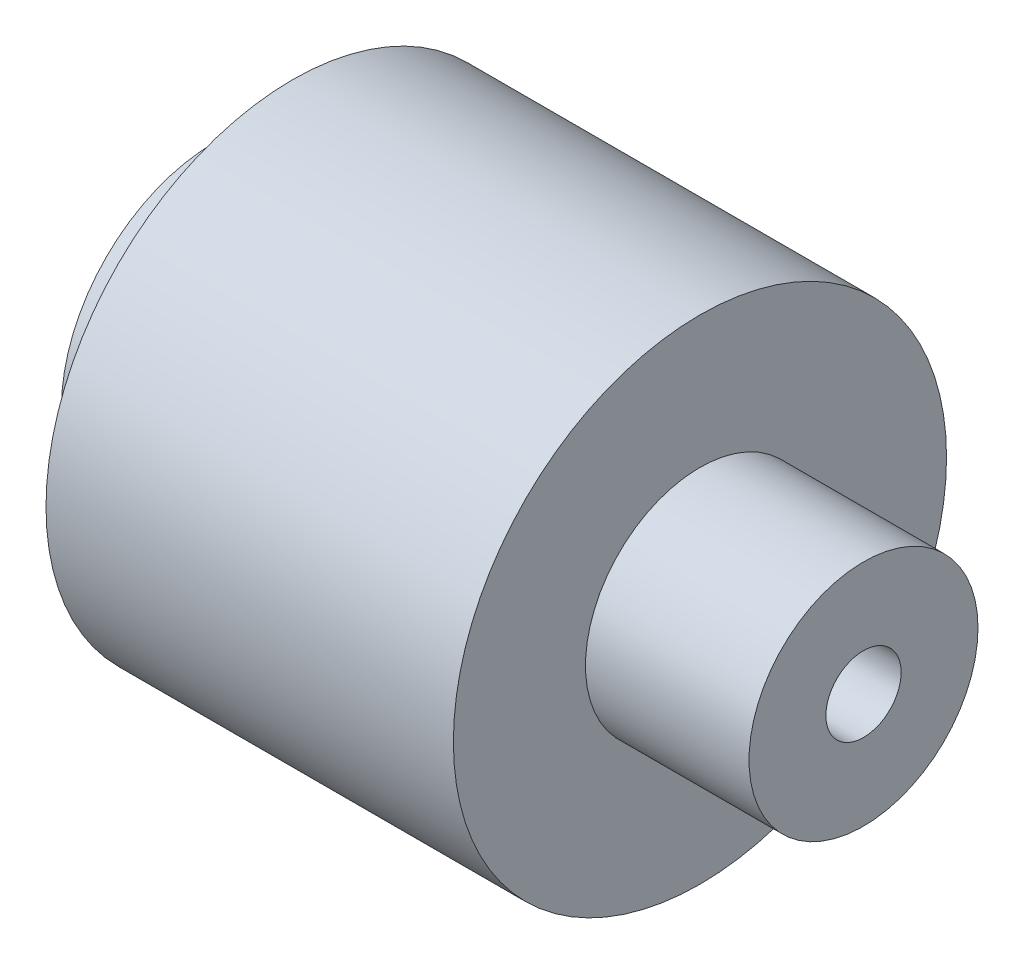
SolidWorks part; units mm, degrees
ref_plane "Front Plane" through (0, 0, 0) normal (0, 0, 1) x (1, 0, 0)
ref_plane "Top Plane" through (0, 0, 0) normal (0, 1, 0) x (1, 0, 0)
ref_plane "Right Plane" through (0, 0, 0) normal (1, 0, 0) x (0, 0, -1)
sketch "Sketch1" plane through (0, 0, 0) normal (1, 0, 0) x (0, 0, -1)
  circle A0 centre (0, 0) radius 15.0762
  dimension "D1" = 30.1523
extrude "Boss-Extrude1" add sketch "Sketch1" along normal blind 34.9072
sketch "Sketch2" plane through (0, 0, 0) normal (-1, 0, 0) x (0, 0, 1)
  circle A0 centre (0, 0) radius 4.5847
  circle A1 centre (0, 0) radius 9.3853
  dimension "D1" = 18.7706
  dimension "D2" = 9.1694
extrude "Boss-Extrude2" add sketch "Sketch2" along normal blind 4.7498
sketch "Sketch3" plane through (34.9072, 0, 0) normal (1, 0, 0) x (0, 0, -1)
  line L0 (-1.775, 1.4627) -> (1.775, 1.4627)
  arc A0 (-1.775, 1.4627) -> (1.775, 1.4627) centre (0, 0) ccw
  dimension "D1" = 4.6
  dimension "D2" = 3.55
extrude "Cut-Extrude1" cut sketch "Sketch3" against normal blind 26
sketch "Sketch4" plane through (34.9072, 0, 0) normal (1, 0, 0) x (0, 0, -1)
  circle A0 centre (0, 0) radius 2.3
  arc A1 (-1.775, 1.4627) -> (1.775, 1.4627) centre (0, 0) ccw construction
extrude "Cut-Extrude2" cut sketch "Sketch4" against normal blind 2.6
sketch "Sketch5" plane through (34.9072, 0, 0) normal (1, 0, 0) x (0, 0, -1)
  circle A0 centre (0, 0) radius 7
  circle A1 centre (0, 0) radius 15.0762
  circle A2 centre (0, 0) radius 15.0762 construction
  dimension "D1" = 14
extrude "Cut-Extrude3" cut sketch "Sketch5" against normal blind 10
